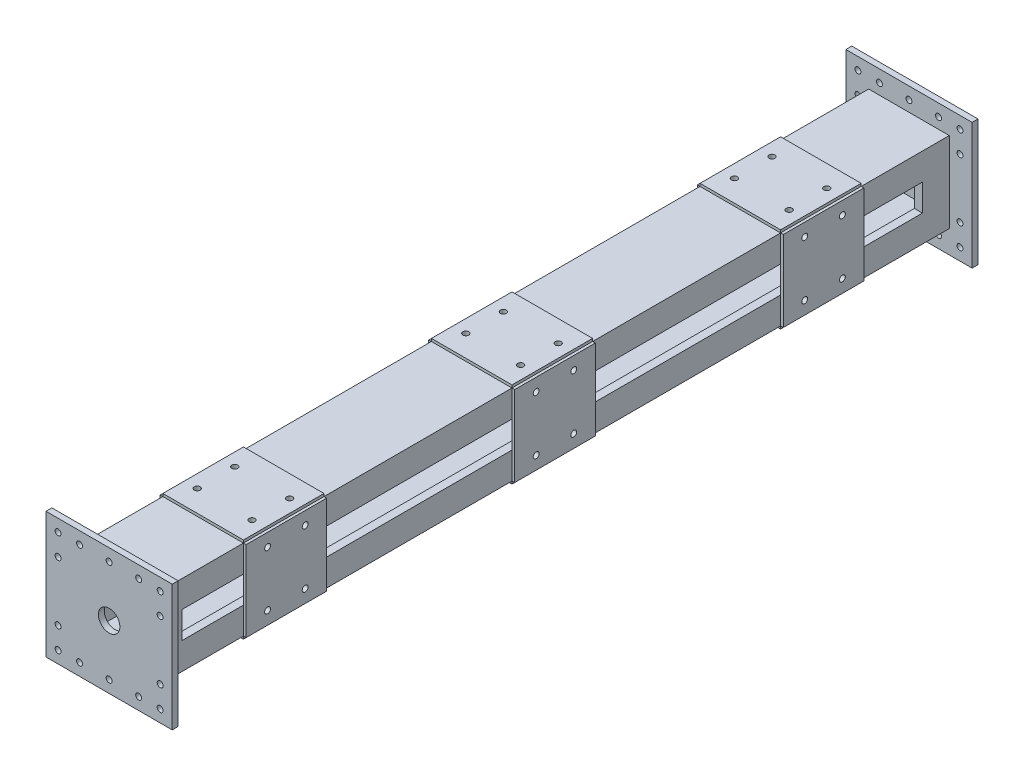
SolidWorks part; units mm, degrees
ref_plane "前视基准面" through (0, 0, 0) normal (0, 0, 1) x (1, 0, 0)
ref_plane "上视基准面" through (0, 0, 0) normal (0, 1, 0) x (1, 0, 0)
ref_plane "右视基准面" through (0, 0, 0) normal (1, 0, 0) x (0, 0, -1)
sketch "草图1" plane through (0, 0, 0) normal (0, 0, 1) x (1, 0, 0)
  line L1 (0, 0) -> (300, 0)
  line L2 (0, 0) -> (0, 300)
  line L3 (0, 300) -> (300, 300)
  line L4 (300, 0) -> (300, 300)
  dimension "D1" = 300
  dimension "D2" = 300
extrude "拉伸1" add sketch "草图1" along normal blind 2956
sketch "草图2" plane through (0, 0, 2956) normal (0, 0, 1) x (1, 0, 0)
  line L0 (300, 300) -> (0, 300) construction
  line L1 (30, 270) -> (270, 270)
  line L2 (30, 270) -> (30, 30)
  line L3 (30, 30) -> (270, 30)
  line L4 (270, 270) -> (270, 30)
  line L5 (0, 0) -> (300, 0) construction
  line L6 (0, 300) -> (0, 0) construction
  line L7 (300, 0) -> (300, 300) construction
  dimension "D1" = 30
  dimension "D2" = 30
  dimension "D3" = 30
  dimension "D4" = 30
extrude "切除-拉伸1" cut sketch "草图2" against normal through all
sketch "草图4" plane through (0, 0, 0) normal (-1, 0, 0) x (0, 0, 1)
  line L0 (0, 300) -> (0, 0) construction
  line L1 (100, 200) -> (2856, 200)
  line L2 (100, 200) -> (100, 100)
  line L3 (100, 100) -> (2856, 100)
  line L4 (2856, 200) -> (2856, 100)
  line L5 (2956, 300) -> (2956, 0) construction
  line L6 (2956, 0) -> (0, 0) construction
  line L7 (2956, 300) -> (0, 300) construction
  dimension "D1" = 100
  dimension "D2" = 100
  dimension "D3" = 100
  dimension "D4" = 100
extrude "切除-拉伸2" cut sketch "草图4" against normal through all
sketch "草图5" plane through (0, 0, 2956) normal (0, 0, 1) x (1, 0, 0)
  line L0 (0, 300) -> (0, 0) construction
  line L1 (-85, 385) -> (385, 385)
  line L2 (-85, 385) -> (-85, -85)
  line L3 (-85, -85) -> (385, -85)
  line L4 (385, 385) -> (385, -85)
  line L5 (0, 0) -> (300, 0) construction
  dimension "D1" = 470
  dimension "D2" = 470
  dimension "D3" = 85
  dimension "D4" = 85
extrude "拉伸2" add sketch "草图5" along normal blind 22
sketch "草图6" plane through (0, 0, 0) normal (0, 0, -1) x (-1, 0, 0)
  line L0 (0, 0) -> (-300, 0) construction
  line L1 (-385, 385) -> (85, 385)
  line L2 (-385, 385) -> (-385, -85)
  line L3 (-385, -85) -> (85, -85)
  line L4 (85, 385) -> (85, -85)
  line L5 (-300, 300) -> (0, 300) construction
  line L6 (-300, 0) -> (-300, 300) construction
  line L7 (0, 300) -> (0, 0) construction
  dimension "D1" = 85
  dimension "D2" = 85
  dimension "D3" = 85
  dimension "D4" = 85
extrude "拉伸3" add sketch "草图6" along normal blind 22
sketch "草图7" plane through (0, 0, 2978) normal (0, 0, 1) x (1, 0, 0)
  line L0 (-85, -85) -> (385, -85) construction
  line L1 (385, -85) -> (385, 385) construction
  circle A0 centre (-40, -40) radius 11
  circle A1 centre (40, -40) radius 11
  circle A2 centre (150, -40) radius 11
  circle A3 centre (260, -40) radius 11
  circle A4 centre (340, -40) radius 11
  circle A5 centre (-40, 340) radius 11
  circle A6 centre (40, 340) radius 11
  circle A7 centre (150, 340) radius 11
  circle A8 centre (260, 340) radius 11
  circle A9 centre (340, 340) radius 11
  circle A10 centre (-40, 40) radius 11
  circle A11 centre (-40, 260) radius 11
  circle A12 centre (340, 40) radius 11
  circle A13 centre (340, 260) radius 11
  dimension "D1" = 80
  dimension "D2" = 80
  dimension "D3" = 220
  dimension "D4" = 45
  dimension "D5" = 80
  dimension "D6" = 80
  dimension "D7" = 110
  dimension "D8" = 110
  dimension "D9" = 45
extrude "切除-拉伸3" cut sketch "草图7" against normal through all
sketch "草图8" plane through (0, 300, 0) normal (0, 1, 0) x (1, 0, 0)
  line L0 (300, -2956) -> (300, 0) construction
  line L1 (0, -328) -> (300, -328)
  line L2 (0, -328) -> (0, -628)
  line L3 (0, -628) -> (300, -628)
  line L4 (300, -328) -> (300, -628)
  line L5 (0, -1328) -> (300, -1328)
  line L6 (0, -1328) -> (0, -1628)
  line L7 (0, -1628) -> (300, -1628)
  line L8 (300, -1328) -> (300, -1628)
  line L9 (0, -2328) -> (300, -2328)
  line L10 (0, -2328) -> (0, -2628)
  line L11 (0, -2628) -> (300, -2628)
  line L12 (300, -2328) -> (300, -2628)
  line L13 (0, -2956) -> (0, 0) construction
  line L14 (300, 0) -> (0, 0) construction
  point P19 (0, -1478)
  dimension "D1" = 300
  dimension "D2" = 300
  dimension "D3" = 300
  dimension "D4" = 700
  dimension "D5" = 700
  dimension "D6" = 150
extrude "拉伸4" add sketch "草图8" along normal blind 10
sketch "草图10" plane through (0, 0, 0) normal (0, -1, 0) x (1, 0, 0)
  line L0 (0, 2956) -> (0, 0) construction
  line L1 (300, 328) -> (0, 328)
  line L2 (300, 328) -> (300, 628)
  line L3 (300, 628) -> (0, 628)
  line L4 (0, 328) -> (0, 628)
  line L5 (300, 1328) -> (0, 1328)
  line L6 (300, 1328) -> (300, 1628)
  line L7 (300, 1628) -> (0, 1628)
  line L8 (0, 1328) -> (0, 1628)
  line L9 (300, 2328) -> (0, 2328)
  line L10 (300, 2328) -> (300, 2628)
  line L11 (300, 2628) -> (0, 2628)
  line L12 (0, 2328) -> (0, 2628)
  line L13 (300, 2956) -> (300, 0) construction
  line L14 (0, 0) -> (300, 0) construction
  point P18 (300, 1478)
  dimension "D1" = 300
  dimension "D2" = 300
  dimension "D3" = 300
  dimension "D4" = 700
  dimension "D5" = 700
  dimension "D6" = 150
extrude "拉伸5" add sketch "草图10" along normal blind 10
sketch "草图11" plane through (300, 0, 0) normal (1, 0, 0) x (0, 0, -1)
  line L1 (-628, 300) -> (-328, 300)
  line L2 (-628, 300) -> (-628, 0)
  line L3 (-628, 0) -> (-328, 0)
  line L4 (-328, 300) -> (-328, 0)
  line L5 (-1628, 0) -> (-1328, 0)
  line L6 (-1628, 0) -> (-1628, 300)
  line L7 (-1628, 300) -> (-1328, 300)
  line L8 (-1328, 0) -> (-1328, 300)
  line L9 (-2628, 300) -> (-2328, 300)
  line L10 (-2628, 300) -> (-2628, 0)
  line L11 (-2628, 0) -> (-2328, 0)
  line L12 (-2328, 300) -> (-2328, 0)
extrude "拉伸6" add sketch "草图11" along normal blind 10
sketch "草图12" plane through (0, 0, 0) normal (-1, 0, 0) x (0, 0, 1)
  line L1 (328, 300) -> (628, 300)
  line L2 (328, 300) -> (328, 0)
  line L3 (328, 0) -> (628, 0)
  line L4 (628, 300) -> (628, 0)
  line L5 (1328, 300) -> (1628, 300)
  line L6 (1328, 300) -> (1328, 0)
  line L7 (1328, 0) -> (1628, 0)
  line L8 (1628, 300) -> (1628, 0)
  line L9 (2328, 300) -> (2628, 300)
  line L10 (2328, 300) -> (2328, 0)
  line L11 (2328, 0) -> (2628, 0)
  line L12 (2628, 300) -> (2628, 0)
extrude "拉伸7" add sketch "草图12" along normal blind 10
sketch "草图13" plane through (0, -10, 0) normal (0, -1, 0) x (1, 0, 0)
  line L0 (300, 2628) -> (0, 2628) construction
  line L1 (0, 2628) -> (0, 2328) construction
  circle A0 centre (48, 2548) radius 11
  point P2 (150, 2628)
  point P5 (0, 2478)
  dimension "D1" = 102
  dimension "D2" = 70
extrude "切除-拉伸4" cut sketch "草图13" against normal through all
pattern_linear "阵列(线性)1" count 2 spacing 204 along (1, 0, 0) count 2 spacing 140 along (0, 0, -1) of "切除-拉伸4"
pattern_linear "阵列(线性)2" count 3 spacing 1000 along (0, 0, -1) of "切除-拉伸4", "阵列(线性)1"
sketch "草图14" plane through (310, 0, 0) normal (1, 0, 0) x (0, 0, -1)
  line L0 (-2628, 0) -> (-2328, 0) construction
  line L1 (-2628, 300) -> (-2628, 0) construction
  circle A0 centre (-2548, 48) radius 11
  point P4 (-2478, 0)
  point P5 (-2628, 150)
  dimension "D1" = 70
  dimension "D2" = 102
extrude "切除-拉伸5" cut sketch "草图14" against normal through all
pattern_linear "阵列(线性)3" count 2 spacing 140 along (0, 0, -1) count 2 spacing 204 along (0, 1, 0) of "切除-拉伸5"
pattern_linear "阵列(线性)4" count 3 spacing 1000 along (0, 0, -1) of "切除-拉伸5", "阵列(线性)3"
sketch "草图15" plane through (0, 0, 2978) normal (0, 0, 1) x (1, 0, 0)
  line L3 (385, 385) -> (-85, 385) construction
  line L7 (-85, 385) -> (-85, -85) construction
  circle A0 centre (150, 150) radius 40
  point P2 (150, 385)
  dimension "D1" = 235
  dimension "D2" = 235
extrude "切除-拉伸6" cut sketch "草图15" against normal through all
